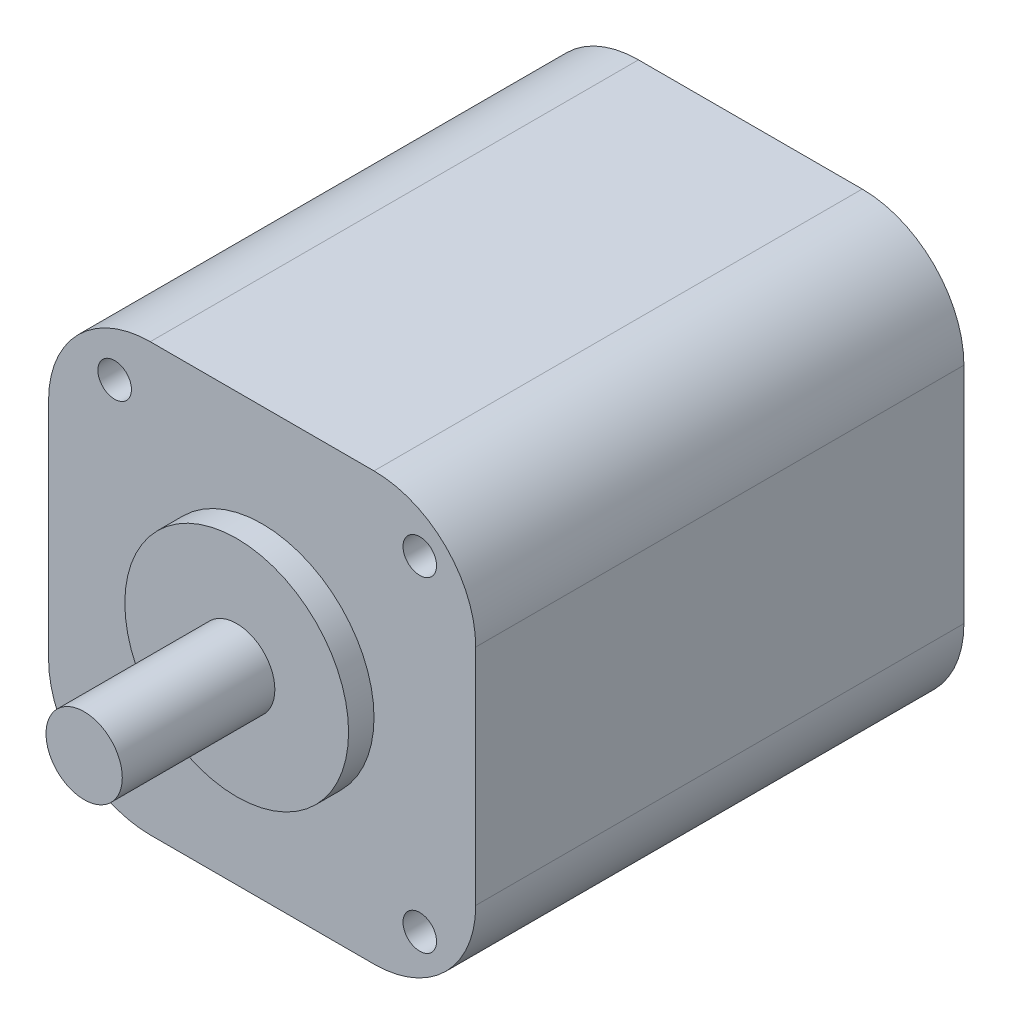
SolidWorks part; units mm, degrees
ref_plane "前视基准面" through (0, 0, 0) normal (0, 0, 1) x (1, 0, 0)
ref_plane "上视基准面" through (0, 0, 0) normal (0, 1, 0) x (1, 0, 0)
ref_plane "右视基准面" through (0, 0, 0) normal (1, 0, 0) x (0, 0, -1)
sketch "草图1" plane through (0, 0, 0) normal (0, 0, 1) x (1, 0, 0)
  line L1 (-45.739, 21.6996) -> (-3.739, 21.6996)
  line L2 (-45.739, 21.6996) -> (-45.739, -20.3004)
  line L3 (-45.739, -20.3004) -> (-3.739, -20.3004)
  line L4 (-3.739, 21.6996) -> (-3.739, -20.3004)
  dimension "D1" = 42
  dimension "D2" = 42
extrude "凸台-拉伸1" add sketch "草图1" along normal blind 48
fillet "圆角1" radius 10 4 edges at (-3.739, -20.3004, 24) (-45.739, -20.3004, 24) (-3.739, 21.6996, 24) (-45.739, 21.6996, 24)
sketch "草图2" plane through (0, 0, 48) normal (0, 0, 1) x (1, 0, 0)
  line L0 (-45.739, 11.6996) -> (-45.739, -10.3004) construction
  line L1 (-35.739, -20.3004) -> (-13.739, -20.3004) construction
  circle A0 centre (-24.739, 0.6996) radius 11
  point P4 (-24.739, -20.3004)
  dimension "D1" = 22
  dimension "D2" = 21
  dimension "D3" = 21
extrude "凸台-拉伸2" add sketch "草图2" along normal blind 2.5
sketch "草图3" plane through (0, 0, 50.5) normal (0, 0, 1) x (1, 0, 0)
  line L0 (-13.739, 21.6996) -> (-35.739, 21.6996) construction
  line L1 (-3.739, -10.3004) -> (-3.739, 11.6996) construction
  circle A0 centre (-24.739, 0.6996) radius 3.75
  point P2 (-24.739, 21.6996)
  dimension "D1" = 7.5
  dimension "D2" = 21
  dimension "D3" = 21
extrude "凸台-拉伸3" add sketch "草图3" along normal blind 15
hole_wizard "M4 螺纹孔1" positions "草图7" profile "草图6" tap size "M4" standard "ISO" end condition through all
sketch "草图7" plane through (0, 0, 0) normal (0, 0, -1) x (-1, 0, 0)
  line L0 (35.739, -20.3004) -> (13.739, -20.3004) construction
  line L1 (13.739, 21.6996) -> (35.739, 21.6996) construction
  line L2 (3.739, -10.3004) -> (3.739, 11.6996) construction
  point P0 (9.239, 16.6996)
  point P1 (9.239, -15.3004)
  point P3 (39.239, -15.3004)
  point P5 (39.239, 16.6996)
  dimension "D1" = 5
  dimension "D2" = 5
  dimension "D3" = 5
  dimension "D4" = 5
  dimension "D5" = 5.5
  dimension "D6" = 5.5
  dimension "D7" = 30
  dimension "D8" = 30
sketch "草图6" plane through (-9.239, 16.6996, 0) normal (1, 0, 0) x (0, 1, 0)
  line L0 (0, 0) -> (0, 65.5)
  line L1 (0, 65.5) -> (1.65, 65.5)
  line L2 (1.65, 65.5) -> (1.65, 0)
  line L5 (1.65, 0) -> (0, 0)
  line L11 (0, -6.35) -> (0, 107.95) construction
  dimension "通孔螺纹孔钻头直径" = 3.3
  dimension "通孔螺纹孔钻头深度" = 65.5
cosmetic thread "孔螺蚊线1" parameters "D2"=4
cosmetic thread "孔螺蚊线2" parameters "D2"=4
cosmetic thread "孔螺蚊线3" parameters "D2"=4
cosmetic thread "孔螺蚊线4" parameters "D2"=4
